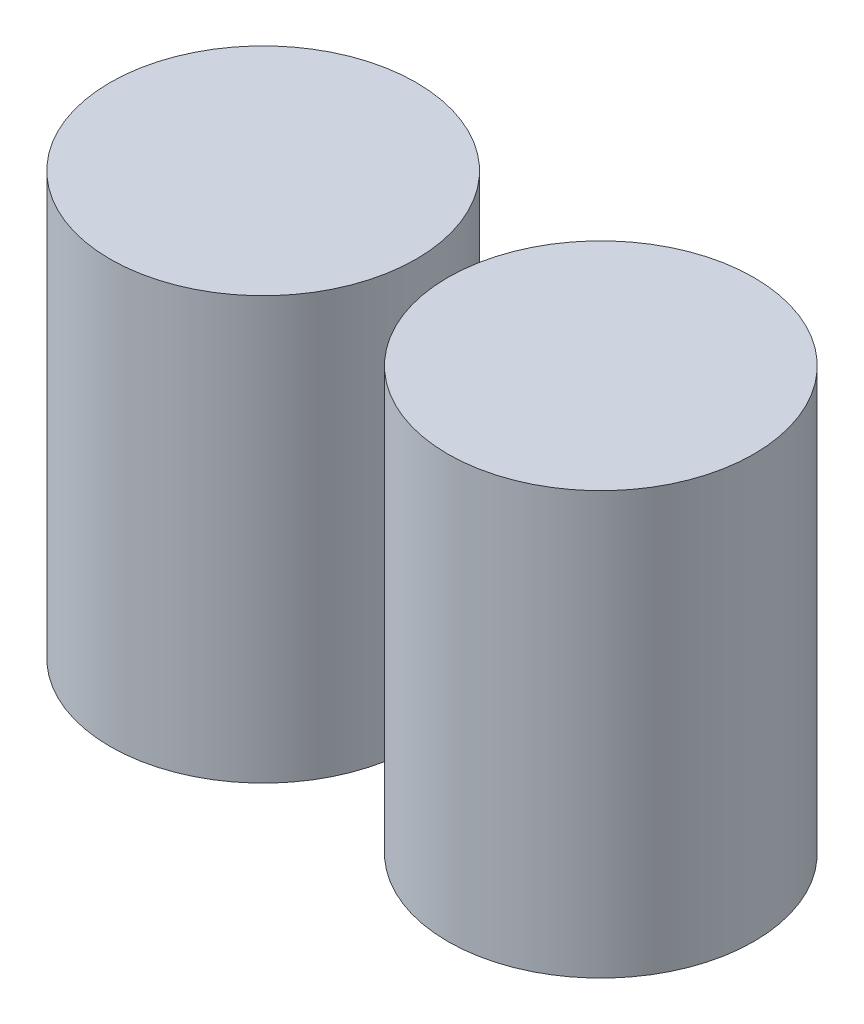
SolidWorks part; units mm, degrees
ref_plane "Front Plane" through (0, 0, 0) normal (0, 0, 1) x (1, 0, 0)
ref_plane "Top Plane" through (0, 0, 0) normal (0, 1, 0) x (1, 0, 0)
ref_plane "Right Plane" through (0, 0, 0) normal (1, 0, 0) x (0, 0, -1)
sketch "Sketch2" plane through (0, 0, 0) normal (0, 1, 0) x (1, 0, 0)
  circle A0 centre (0, 0) radius 14.5
  circle A1 centre (32, 0) radius 14.5
  dimension "D1" = 29
  dimension "D2" = 2
extrude "Boss-Extrude1" add sketch "Sketch2" along normal blind 40
